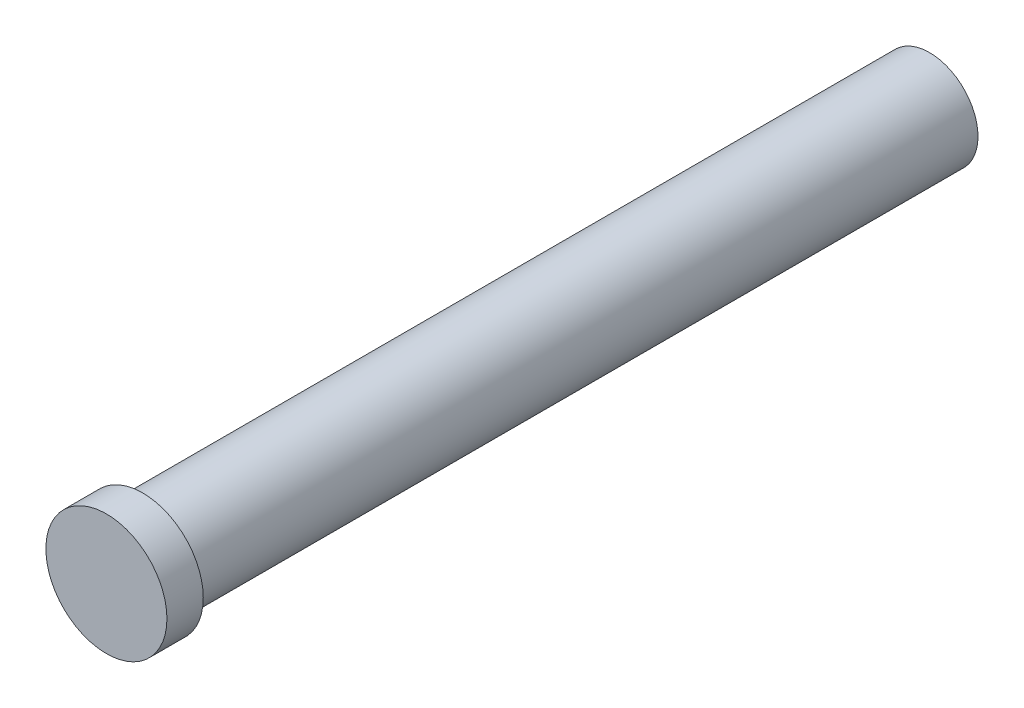
SolidWorks part; units mm, degrees
ref_plane "Front Plane" through (0, 0, 0) normal (0, 0, 1) x (1, 0, 0)
ref_plane "Top Plane" through (0, 0, 0) normal (0, 1, 0) x (1, 0, 0)
ref_plane "Right Plane" through (0, 0, 0) normal (1, 0, 0) x (0, 0, -1)
sketch "Sketch1" plane through (0, 0, 0) normal (0, 0, 1) x (1, 0, 0)
  circle A0 centre (0, 0) radius 4
  dimension "D1" = 8
extrude "Boss-Extrude1" add sketch "Sketch1" along normal blind 65
sketch "Sketch2" plane through (0, 0, 65) normal (0, 0, 1) x (1, 0, 0)
  circle A0 centre (0, 0) radius 5
  dimension "D1" = 10
extrude "Boss-Extrude2" add sketch "Sketch2" along normal blind 3
